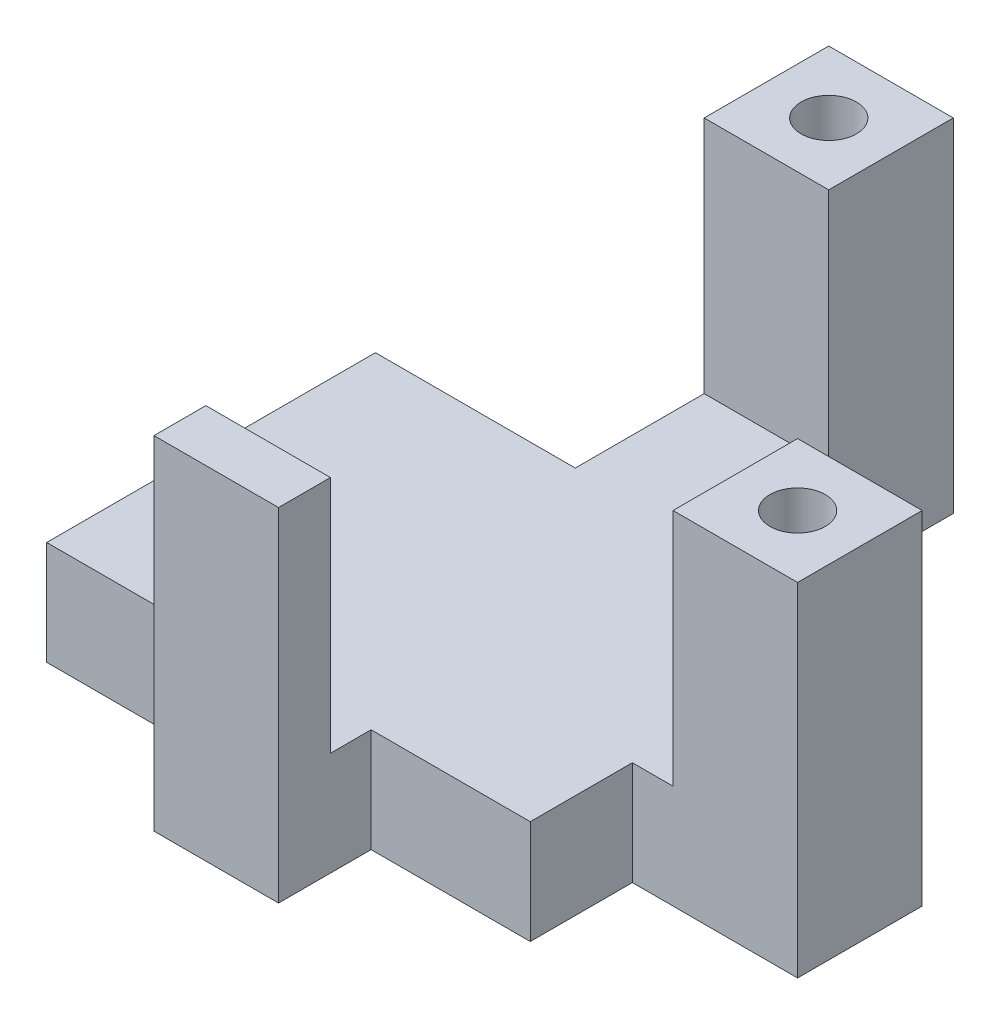
SolidWorks part; units mm, degrees
ref_plane "Front Plane" through (0, 0, 0) normal (0, 0, 1) x (1, 0, 0)
ref_plane "Top Plane" through (0, 0, 0) normal (0, 1, 0) x (1, 0, 0)
ref_plane "Right Plane" through (0, 0, 0) normal (1, 0, 0) x (0, 0, -1)
sketch "Sketch1" plane through (0, 0, 0) normal (0, 0, 1) x (1, 0, 0)
  line L0 (0, 0) -> (68.05, 0)
  line L1 (68.05, 0) -> (68.05, -3)
  line L2 (68.05, -3) -> (0, -3)
  line L3 (0, -3) -> (0, 0)
  dimension "D1" = 68.05
  dimension "D2" = 3
extrude "Boss-Extrude1" add sketch "Sketch1" along normal blind 3
sketch "Sketch5" plane through (0, -3, 0) normal (0, -1, 0) x (1, 0, 0)
  line L0 (0, 0) -> (68.05, 0) construction
  line L1 (68.05, 3) -> (65.05, 3)
  line L2 (68.05, 3) -> (68.05, 0)
  line L3 (68.05, 0) -> (65.05, 0)
  line L4 (65.05, 3) -> (65.05, 0)
  dimension "D1" = 3
extrude "Boss-Extrude2" add sketch "Sketch5" along normal blind 16.8
sketch "Sketch6" plane through (65.05, 0, 0) normal (-1, 0, 0) x (0, 0, 1)
  line L0 (3, -19.8) -> (3, -3) construction
  line L1 (0, -19.8) -> (3, -19.8)
  line L2 (0, -19.8) -> (0, -16.8)
  line L3 (0, -16.8) -> (3, -16.8)
  line L4 (3, -19.8) -> (3, -16.8)
  dimension "D1" = 3
extrude "Boss-Extrude3" add sketch "Sketch6" along normal blind 30.3
sketch "Sketch8" plane through (0, 0, 3) normal (0, 0, 1) x (1, 0, 0)
  line L0 (34.75, -3) -> (34.75, 0)
  line L1 (0, -3) -> (65.05, -3) construction
  line L2 (68.05, 0) -> (0, 0) construction
  line L3 (34.75, 0) -> (68.05, 0)
  line L4 (68.05, 0) -> (68.05, -19.8)
  line L5 (68.05, -19.8) -> (34.75, -19.8)
  line L6 (34.75, -19.8) -> (34.75, -16.8)
  line L7 (34.75, -16.8) -> (65.05, -16.8)
  line L8 (65.05, -16.8) -> (65.05, -3)
  line L9 (65.05, -3) -> (34.75, -3)
extrude "Boss-Extrude4" add sketch "Sketch8" along normal blind 16
sketch "Sketch10" plane through (0, -19.8, 0) normal (0, -1, 0) x (1, 0, 0)
  line L1 (34.75, 19) -> (68.05, 19)
  line L2 (34.75, 19) -> (34.75, 0)
  line L3 (34.75, 0) -> (68.05, 0)
  line L4 (68.05, 19) -> (68.05, 0)
extrude "Boss-Extrude5" add sketch "Sketch10" along normal blind 3
sketch "Sketch12" plane through (0, 0, 0) normal (0, 1, 0) x (1, 0, 0)
  line L0 (0, 0) -> (0, -3)
  line L1 (0, -3) -> (34.75, -3)
  line L2 (34.75, -3) -> (34.75, -19)
  line L3 (34.75, -19) -> (68.05, -19)
  line L4 (68.05, -19) -> (68.05, 0)
  line L5 (68.05, 0) -> (0, 0)
extrude "Boss-Extrude6" add sketch "Sketch12" along normal blind 3.05
sketch "Sketch13" plane through (0, 0, 0) normal (0, 0, -1) x (-1, 0, 0)
  line L0 (0, 3.05) -> (0, -3) construction
  line L1 (-68.05, 3.05) -> (0, 3.05) construction
  circle A0 centre (-4.875, -0.8) radius 2.85
  dimension "D1" = 5.7
  dimension "D2" = 3.85
  dimension "D3" = 4.875
extrude "Cut-Extrude1" cut sketch "Sketch13" against normal blind 21.5
sketch "Sketch14" plane through (0, 0, 0) normal (0, 0, -1) x (-1, 0, 0)
  line L0 (-68.05, 3.05) -> (0, 3.05) construction
  line L1 (-62.05, 3.05) -> (-59.05, 3.05)
  line L2 (-62.05, 3.05) -> (-62.05, -3)
  line L3 (-62.05, -3) -> (-59.05, -3)
  line L4 (-59.05, 3.05) -> (-59.05, -3)
  line L5 (0, -3) -> (-3.0632, -3) construction
  line L6 (-68.05, -22.8) -> (-68.05, 3.05) construction
  line L7 (-40.75, 3.05) -> (-37.75, 3.05)
  line L8 (-40.75, 3.05) -> (-40.75, -3)
  line L9 (-40.75, -3) -> (-37.75, -3)
  line L10 (-37.75, 3.05) -> (-37.75, -3)
  line L11 (-34.75, -16.8) -> (-34.75, -22.8) construction
  line L12 (-34.75, -16.8) -> (-65.05, -16.8) construction
  line L13 (-51.4, 3.05) -> (-48.4, 3.05)
  line L14 (-51.4, 3.05) -> (-51.4, -3)
  line L15 (-51.4, -3) -> (-48.4, -3)
  line L16 (-48.4, 3.05) -> (-48.4, -3)
  line L17 (-62.05, -16.8) -> (-59.05, -16.8)
  line L18 (-62.05, -16.8) -> (-62.05, -22.8)
  line L19 (-62.05, -22.8) -> (-59.05, -22.8)
  line L20 (-59.05, -16.8) -> (-59.05, -22.8)
  line L21 (-34.75, -22.8) -> (-68.05, -22.8) construction
  line L23 (-51.4, -16.8) -> (-48.4, -16.8)
  line L24 (-51.4, -16.8) -> (-51.4, -22.8)
  line L25 (-51.4, -22.8) -> (-48.4, -22.8)
  line L26 (-48.4, -16.8) -> (-48.4, -22.8)
  line L27 (-40.75, -16.8) -> (-37.75, -16.8)
  line L28 (-40.75, -16.8) -> (-40.75, -22.8)
  line L29 (-40.75, -22.8) -> (-37.75, -22.8)
  line L30 (-37.75, -16.8) -> (-37.75, -22.8)
  dimension "D1" = 6
  dimension "D2" = 6
  dimension "D3" = 3
  dimension "D4" = 3
  dimension "D5" = 3
  dimension "D6" = 7.65
extrude "Boss-Extrude7" add sketch "Sketch14" along normal blind 10.45
sketch "Sketch15" plane through (0, -16.8, 0) normal (0, 1, 0) x (1, 0, 0)
  line L0 (62.05, 10.45) -> (62.05, 0) construction
  line L1 (59.05, 10.45) -> (62.05, 10.45)
  line L2 (59.05, 10.45) -> (59.05, 7.45)
  line L3 (59.05, 7.45) -> (62.05, 7.45)
  line L4 (62.05, 10.45) -> (62.05, 7.45)
  line L5 (51.4, 10.45) -> (51.4, 0) construction
  line L6 (48.4, 10.45) -> (51.4, 10.45)
  line L7 (48.4, 10.45) -> (48.4, 7.45)
  line L8 (48.4, 7.45) -> (51.4, 7.45)
  line L9 (51.4, 10.45) -> (51.4, 7.45)
  line L10 (40.75, 10.45) -> (40.75, 0) construction
  line L11 (37.75, 10.45) -> (40.75, 10.45)
  line L12 (37.75, 10.45) -> (37.75, 7.45)
  line L13 (37.75, 7.45) -> (40.75, 7.45)
  line L14 (40.75, 10.45) -> (40.75, 7.45)
  dimension "D1" = 3
  dimension "D2" = 3
  dimension "D3" = 3
extrude "Boss-Extrude8" add sketch "Sketch15" along normal up to surface (13.8 mm away) up to face at (45.0985, -3, -1.0389)
sketch "Sketch16" plane through (0, 0, 19) normal (0, 0, 1) x (1, 0, 0)
  line L0 (34.75, -3) -> (65.05, -3) construction
  line L1 (37.75, -3) -> (40.75, -3)
  line L2 (37.75, -3) -> (37.75, 3.05)
  line L3 (37.75, 3.05) -> (40.75, 3.05)
  line L4 (40.75, -3) -> (40.75, 3.05)
  line L5 (34.75, 3.05) -> (68.05, 3.05) construction
  line L6 (68.05, -22.8) -> (68.05, 3.05) construction
  line L7 (48.4, 3.05) -> (51.4, 3.05)
  line L8 (48.4, 3.05) -> (48.4, -3)
  line L9 (48.4, -3) -> (51.4, -3)
  line L10 (51.4, 3.05) -> (51.4, -3)
  line L11 (59.05, 3.05) -> (62.05, 3.05)
  line L12 (59.05, 3.05) -> (59.05, -3)
  line L13 (59.05, -3) -> (62.05, -3)
  line L14 (62.05, 3.05) -> (62.05, -3)
  line L15 (34.75, 3.05) -> (34.75, -3) construction
  line L16 (65.05, -16.8) -> (34.75, -16.8) construction
  line L17 (37.75, -16.8) -> (40.75, -16.8)
  line L18 (37.75, -16.8) -> (37.75, -22.8)
  line L19 (37.75, -22.8) -> (40.75, -22.8)
  line L20 (40.75, -16.8) -> (40.75, -22.8)
  line L21 (68.05, -22.8) -> (34.75, -22.8) construction
  line L23 (48.4, -16.8) -> (51.4, -16.8)
  line L24 (48.4, -16.8) -> (48.4, -22.8)
  line L25 (48.4, -22.8) -> (51.4, -22.8)
  line L26 (51.4, -16.8) -> (51.4, -22.8)
  line L27 (59.05, -16.8) -> (62.05, -16.8)
  line L28 (59.05, -16.8) -> (59.05, -22.8)
  line L29 (59.05, -22.8) -> (62.05, -22.8)
  line L30 (62.05, -16.8) -> (62.05, -22.8)
  dimension "D1" = 6
  dimension "D2" = 3
  dimension "D3" = 3
  dimension "D4" = 3
  dimension "D5" = 7.65
  dimension "D6" = 3
extrude "Boss-Extrude9" add sketch "Sketch16" along normal blind 5.35
sketch "Sketch17" plane through (0, -16.8, 0) normal (0, 1, 0) x (1, 0, 0)
  line L0 (40.75, -24.35) -> (40.75, -19) construction
  line L1 (37.75, -24.35) -> (40.75, -24.35)
  line L2 (37.75, -24.35) -> (37.75, -21.35)
  line L3 (37.75, -21.35) -> (40.75, -21.35)
  line L4 (40.75, -24.35) -> (40.75, -21.35)
  line L5 (51.4, -24.35) -> (51.4, -19) construction
  line L6 (48.4, -24.35) -> (51.4, -24.35)
  line L7 (48.4, -24.35) -> (48.4, -21.35)
  line L8 (48.4, -21.35) -> (51.4, -21.35)
  line L9 (51.4, -24.35) -> (51.4, -21.35)
  line L10 (62.05, -24.35) -> (62.05, -19) construction
  line L11 (59.05, -24.35) -> (62.05, -24.35)
  line L12 (59.05, -24.35) -> (59.05, -21.35)
  line L13 (59.05, -21.35) -> (62.05, -21.35)
  line L14 (62.05, -24.35) -> (62.05, -21.35)
  dimension "D1" = 3
  dimension "D2" = 3
  dimension "D3" = 3
extrude "Boss-Extrude10" add sketch "Sketch17" along normal up to surface (13.8 mm away) up to face at (47.0191, -3, 8.6467)
sketch "Sketch20" plane through (68.05, 0, 0) normal (1, 0, 0) x (0, 0, -1)
  line L0 (0, -22.8) -> (0, 3.05) construction
  line L1 (-3, -17.7) -> (-11.95, -17.7)
  line L2 (-3, -17.7) -> (-3, -11.7)
  line L3 (-3, -11.7) -> (-11.95, -11.7)
  line L4 (-11.95, -17.7) -> (-11.95, -11.7)
  line L5 (0, -22.8) -> (-19, -22.8) construction
  dimension "D1" = 3
  dimension "D2" = 5.1
  dimension "D3" = 6
  dimension "D4" = 8.95
extrude "Boss-Extrude12" add sketch "Sketch20" along normal blind 19.6
sketch "Sketch22" plane through (0, -11.7, 0) normal (0, 1, 0) x (1, 0, 0)
  line L0 (87.65, -3) -> (68.05, -3) construction
  line L1 (87.65, -3) -> (87.65, -11.95) construction
  circle A0 centre (83.8, -7.95) radius 2.85
  dimension "D1" = 5.7
  dimension "D2" = 4.95
  dimension "D3" = 3.85
extrude "Cut-Extrude3" cut sketch "Sketch22" against normal through all
sketch "Sketch23" plane through (0, 0, 0) normal (-1, 0, 0) x (0, 0, 1)
  line L1 (0, 3.05) -> (3, 3.05)
  line L2 (0, 3.05) -> (0, -3)
  line L3 (0, -3) -> (3, -3)
  line L4 (3, 3.05) -> (3, -3)
extrude "Cut-Extrude4" cut sketch "Sketch23" against normal up to surface (34.75 mm away) up to face at (34.75, 0.025, 11)
sketch "Sketch24" plane through (87.65, 0, 0) normal (1, 0, 0) x (0, 0, -1)
  line L1 (-11.95, -11.7) -> (-3, -11.7)
  line L2 (-11.95, -11.7) -> (-11.95, -17.7)
  line L3 (-11.95, -17.7) -> (-3, -17.7)
  line L4 (-3, -11.7) -> (-3, -17.7)
extrude "Cut-Extrude5" cut sketch "Sketch24" against normal up to surface (19.6 mm away) up to face at (68.05, -9.875, 9.5)
sketch "Sketch25" plane through (0, 3.05, 0) normal (0, 1, 0) x (1, 0, 0)
  line L0 (34.75, 0) -> (34.75, -19)
  line L1 (34.75, -19) -> (68.05, -19)
  line L2 (68.05, -19) -> (68.05, 0)
  line L3 (68.05, 0) -> (34.75, 0)
extrude "Cut-Extrude7" cut sketch "Sketch25" against normal up to surface (6.05 mm away) contours L3 L0 L1 L2 up to face at (49.9, -3, 8.4071)
sketch "Sketch27" plane through (0, 3.05, 0) normal (0, 1, 0) x (1, 0, 0)
  line L0 (40.75, -24.35) -> (40.75, -19) construction
  line L1 (37.75, 10.45) -> (40.75, 10.45)
  line L2 (37.75, 10.45) -> (37.75, 0)
  line L3 (37.75, 0) -> (40.75, 0)
  line L4 (40.75, 10.45) -> (40.75, 0)
  line L5 (37.75, -19) -> (40.75, -19)
  line L6 (37.75, -19) -> (37.75, -24.35)
  line L7 (37.75, -24.35) -> (40.75, -24.35)
  line L8 (40.75, -19) -> (40.75, -24.35)
  line L10 (59.05, 10.45) -> (62.05, 10.45)
  line L11 (59.05, 10.45) -> (59.05, 0)
  line L12 (59.05, 0) -> (62.05, 0)
  line L13 (62.05, 10.45) -> (62.05, 0)
  line L14 (59.05, -19) -> (62.05, -19)
  line L15 (59.05, -19) -> (59.05, -24.35)
  line L16 (59.05, -24.35) -> (62.05, -24.35)
  line L17 (62.05, -19) -> (62.05, -24.35)
extrude "Cut-Extrude8" cut sketch "Sketch27" against normal up to surface (25.85 mm away) up to face at (50.1143, -22.8, 8.4071)
sketch "Sketch28" plane through (0, 0, 19) normal (0, 0, 1) x (1, 0, 0)
  line L1 (65.05, -16.8) -> (68.05, -16.8)
  line L2 (65.05, -16.8) -> (65.05, -3)
  line L3 (65.05, -3) -> (68.05, -3)
  line L4 (68.05, -16.8) -> (68.05, -3)
extrude "Cut-Extrude9" cut sketch "Sketch28" against normal blind 19
sketch "Sketch29" plane through (0, 3.05, 0) normal (0, 1, 0) x (1, 0, 0)
  line L1 (48.4, 10.45) -> (51.4, 10.45)
  line L2 (48.4, 10.45) -> (48.4, 0)
  line L3 (48.4, 0) -> (51.4, 0)
  line L4 (51.4, 10.45) -> (51.4, 0)
  line L5 (48.4, -19) -> (51.4, -19)
  line L6 (48.4, -19) -> (48.4, -24.35)
  line L7 (48.4, -24.35) -> (51.4, -24.35)
  line L8 (51.4, -19) -> (51.4, -24.35)
extrude "Cut-Extrude10" cut sketch "Sketch29" against normal blind 6.05
sketch "Sketch30" plane through (48.4, 0, 0) normal (-1, 0, 0) x (0, 0, 1)
  line L0 (-10.45, -3) -> (-10.45, -22.8)
  line L1 (-10.45, -22.8) -> (0, -22.8)
  line L2 (0, -22.8) -> (0, -16.8)
  line L3 (0, -16.8) -> (-7.45, -16.8)
  line L4 (-7.45, -16.8) -> (-7.45, -3)
  line L5 (-7.45, -3) -> (-10.45, -3)
  line L6 (21.35, -3) -> (21.35, -16.8)
  line L7 (21.35, -16.8) -> (19, -16.8)
  line L8 (19, -16.8) -> (19, -22.8)
  line L9 (19, -22.8) -> (24.35, -22.8)
  line L10 (24.35, -22.8) -> (24.35, -3)
  line L11 (24.35, -3) -> (21.35, -3)
extrude "Boss-Extrude13" add sketch "Sketch30" along normal blind 2.1
sketch "Sketch31" plane through (51.4, 0, 0) normal (1, 0, 0) x (0, 0, -1)
  line L0 (-24.35, -3) -> (-24.35, -22.8)
  line L1 (-24.35, -22.8) -> (-19, -22.8)
  line L2 (-19, -22.8) -> (-19, -16.8)
  line L3 (-19, -16.8) -> (-21.35, -16.8)
  line L4 (-21.35, -16.8) -> (-21.35, -3)
  line L5 (-21.35, -3) -> (-24.35, -3)
  line L6 (7.45, -3) -> (10.45, -3)
  line L7 (10.45, -3) -> (10.45, -22.8)
  line L8 (10.45, -22.8) -> (0, -22.8)
  line L9 (0, -22.8) -> (0, -16.8)
  line L10 (0, -16.8) -> (7.45, -16.8)
  line L11 (7.45, -16.8) -> (7.45, -3)
extrude "Boss-Extrude14" add sketch "Sketch31" along normal blind 2.1
sketch "Sketch32" plane through (0, 0, -10.45) normal (0, 0, -1) x (-1, 0, 0)
  line L1 (-53.5, -3) -> (-46.3, -3)
  line L2 (-53.5, -3) -> (-53.5, -22.8)
  line L3 (-53.5, -22.8) -> (-46.3, -22.8)
  line L4 (-46.3, -3) -> (-46.3, -22.8)
extrude "Boss-Extrude15" add sketch "Sketch32" along normal blind 4.2
sketch "Sketch33" plane through (0, -22.8, 0) normal (0, -1, 0) x (1, 0, 0)
  line L0 (53.5, -14.65) -> (46.3, -14.65) construction
  line L1 (46.3, -14.65) -> (46.3, 0) construction
  circle A0 centre (49.9, -11.05) radius 1.6
  dimension "D1" = 3.2
  dimension "D2" = 3.6
  dimension "D3" = 3.6
extrude "Cut-Extrude11" cut sketch "Sketch33" against normal through all contours A0
sketch "Sketch34" plane through (68.05, 0, 0) normal (1, 0, 0) x (0, 0, -1)
  line L1 (-19, -16.8) -> (0, -16.8)
  line L2 (-19, -16.8) -> (-19, -22.8)
  line L3 (-19, -22.8) -> (0, -22.8)
  line L4 (0, -16.8) -> (0, -22.8)
extrude "Cut-Extrude12" cut sketch "Sketch34" against normal blind 5.35
sketch "Sketch36" plane through (62.7, 0, 0) normal (1, 0, 0) x (0, 0, -1)
  line L0 (0, -16.8) -> (-19, -16.8) construction
  line L1 (-13.1, -16.8) -> (-5.9, -16.8)
  line L2 (-13.1, -16.8) -> (-13.1, -22.8)
  line L3 (-13.1, -22.8) -> (-5.9, -22.8)
  line L4 (-5.9, -16.8) -> (-5.9, -22.8)
  line L5 (-19, -22.8) -> (0, -22.8) construction
  line L6 (0, -22.8) -> (0, -16.8) construction
  dimension "D1" = 7.2
  dimension "D2" = 5.9
extrude "Boss-Extrude16" add sketch "Sketch36" along normal blind 9.55
sketch "Sketch37" plane through (0, -16.8, 0) normal (0, 1, 0) x (1, 0, 0)
  line L0 (72.25, -13.1) -> (62.7, -13.1) construction
  line L1 (72.25, -5.9) -> (65.05, -5.9)
  line L2 (72.25, -5.9) -> (72.25, -13.1)
  line L3 (72.25, -13.1) -> (65.05, -13.1)
  line L4 (65.05, -5.9) -> (65.05, -13.1)
  dimension "D1" = 7.2
extrude "Boss-Extrude17" add sketch "Sketch37" along normal up to surface (13.8 mm away) up to face at (51.5, -3, -11.05)
sketch "Sketch39" plane through (0, -3, 0) normal (0, 1, 0) x (1, 0, 0)
  line L0 (72.25, -13.1) -> (72.25, -5.9) construction
  line L1 (72.25, -5.9) -> (65.05, -5.9) construction
  circle A0 centre (68.65, -9.5) radius 1.6
  dimension "D1" = 3.2
  dimension "D2" = 3.6
  dimension "D3" = 3.6
extrude "Cut-Extrude13" cut sketch "Sketch39" against normal up to surface (19.8 mm away) contours A0 up to face at (51.5, -22.8, -11.05)
